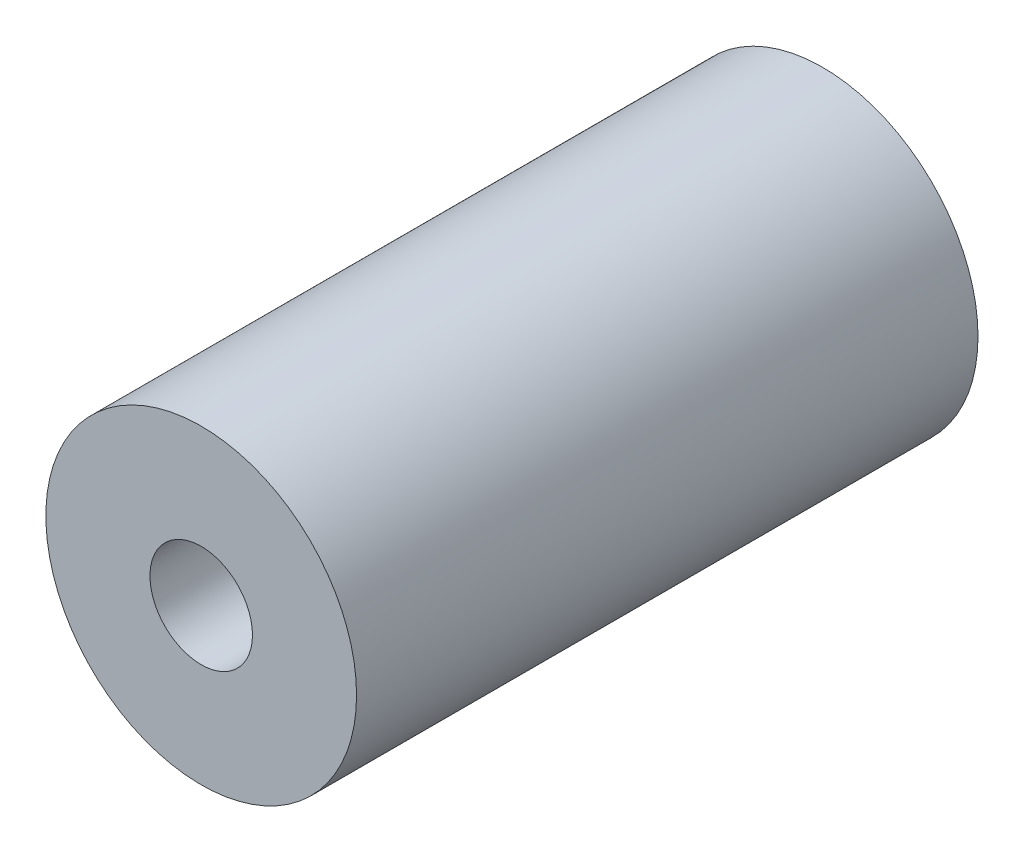
SolidWorks part; units mm, degrees
ref_plane "前视基准面" through (0, 0, 0) normal (0, 0, 1) x (1, 0, 0)
ref_plane "上视基准面" through (0, 0, 0) normal (0, 1, 0) x (1, 0, 0)
ref_plane "右视基准面" through (0, 0, 0) normal (1, 0, 0) x (0, 0, -1)
sketch "草图1" plane through (0, 0, 0) normal (0, 0, 1) x (1, 0, 0)
  circle A0 centre (0, 0) radius 50
  circle A1 centre (0, 0) radius 16.5
  dimension "D1" = 100
  dimension "D2" = 33
extrude "凸台-拉伸1" add sketch "草图1" along normal blind 200
